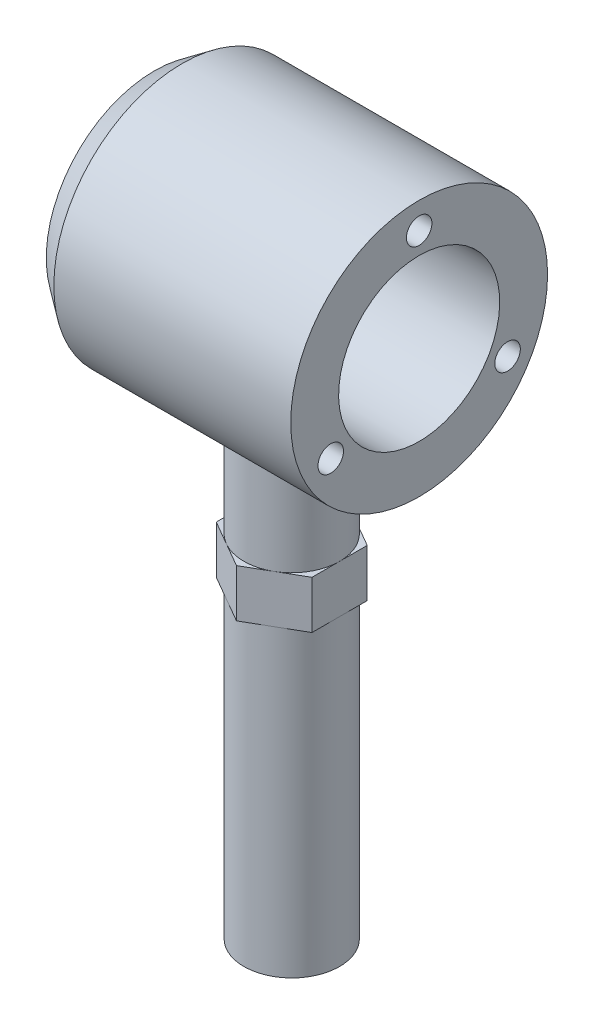
SolidWorks part; units mm, degrees
ref_plane "Front Plane" through (0, 0, 0) normal (0, 0, 1) x (1, 0, 0)
ref_plane "Top Plane" through (0, 0, 0) normal (0, 1, 0) x (1, 0, 0)
ref_plane "Right Plane" through (0, 0, 0) normal (1, 0, 0) x (0, 0, -1)
sketch "Sketch1" plane through (0, 0, 0) normal (0, 0, 1) x (1, 0, 0)
  line L0 (8.5235, 15) -> (-1.1649, 20.895)
  line L1 (-1.1649, 20.895) -> (-1.1649, 33.8804)
  line L2 (-1.1649, 33.8804) -> (7.5733, 40.25)
  line L3 (7.5733, 40.25) -> (81.8351, 40.25)
  line L4 (81.8351, 40.25) -> (81.8351, 25.25)
  line L5 (81.8351, 25.25) -> (28.8351, 25.25)
  line L6 (28.8351, 0) -> (-34.837, 0) construction
  arc A0 (28.8351, 25.25) -> (8.5235, 15) centre (28.8351, 0) ccw
  dimension "D1" = 50.5
  dimension "D6" = 25.25
  dimension "D2" = 15
  dimension "D3" = 15
  dimension "D4" = 30
  dimension "D5" = 53
revolve "Revolve1" add sketch "Sketch1" angle 360 about L6
ref_plane "Plane1" through (0, -40.25, 0) normal (0, -1, 0) x (-1, 0, 0)
sketch "Sketch2" plane through (0, -40.25, 0) normal (0, -1, 0) x (-1, 0, 0)
  circle A0 centre (-41.8971, 0) radius 15
  dimension "D1" = 30
extrude "Boss-Extrude1" add sketch "Sketch2" along normal blind 30 and the other way up to surface other way up to face at (7.5733, 40.25, 0)
sketch "Sketch3" plane through (0, -70.25, 0) normal (0, -1, 0) x (1, 0, 0)
  line L0 (7.5733, 40.25) -> (7.5733, -40.25) construction
  line L1 (56.8971, -8.6603) -> (56.8971, 8.6603)
  line L2 (56.8971, 8.6603) -> (41.8971, 17.3205)
  line L3 (41.8971, 17.3205) -> (26.8971, 8.6603)
  line L4 (26.8971, 8.6603) -> (26.8971, -8.6603)
  line L5 (26.8971, -8.6603) -> (41.8971, -17.3205)
  line L6 (41.8971, -17.3205) -> (56.8971, -8.6603)
  circle A0 centre (41.8971, 0) radius 15 construction
  circle A1 centre (41.8971, 0) radius 15 construction
  dimension "D1" = 30
extrude "Boss-Extrude2" add sketch "Sketch3" along normal blind 15
sketch "Sketch4" plane through (0, -85.25, 0) normal (0, -1, 0) x (1, 0, 0)
  circle A0 centre (41.8971, 0) radius 15
extrude "Boss-Extrude3" add sketch "Sketch4" along normal blind 95
sketch "Sketch5" plane through (81.8351, 0, 0) normal (1, 0, 0) x (0, 0, -1)
  circle A0 centre (0, 32) radius 4
  circle A1 centre (27.7128, -16) radius 4
  circle A2 centre (-27.7128, -16) radius 4
  point P10 (0, 0)
  dimension "D1" = 8
  dimension "D2" = 32
  dimension "D3" = 3
extrude "Cut-Extrude1" cut sketch "Sketch5" against normal blind 20
